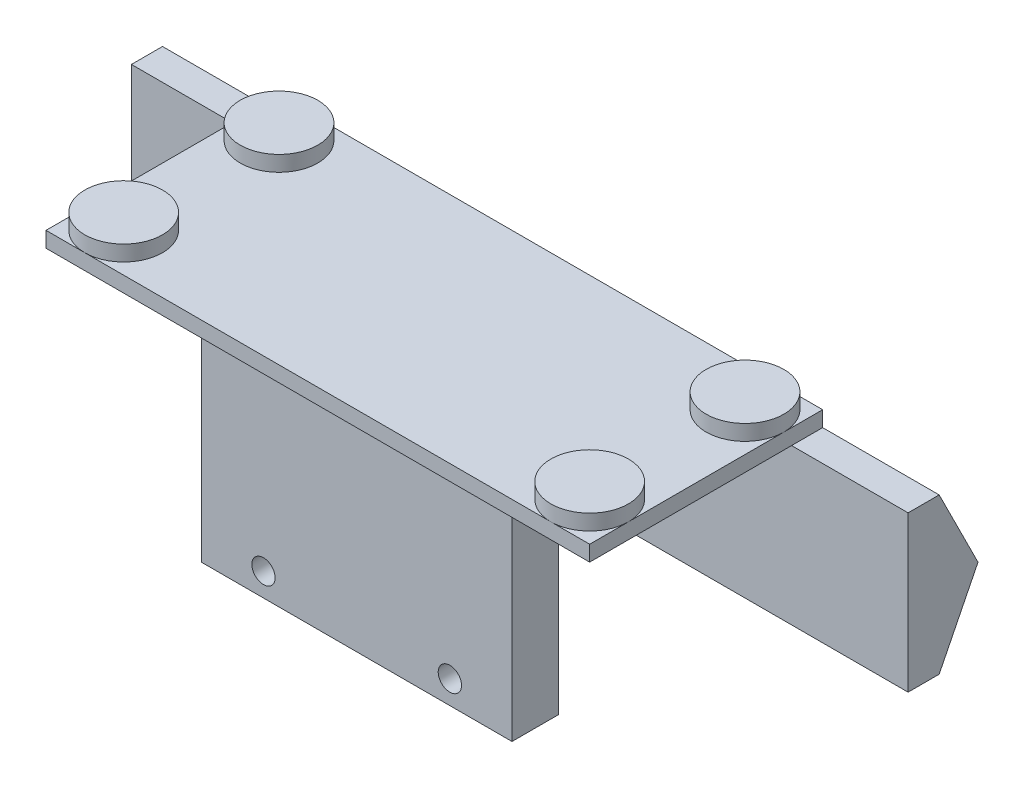
SolidWorks part; units mm, degrees
ref_plane "前视基准面" through (0, 0, 0) normal (0, 0, 1) x (1, 0, 0)
ref_plane "上视基准面" through (0, 0, 0) normal (0, 1, 0) x (1, 0, 0)
ref_plane "右视基准面" through (0, 0, 0) normal (1, 0, 0) x (0, 0, -1)
sketch "草图1" plane through (0, 0, 0) normal (0, 1, 0) x (1, 0, 0)
  line L0 (0, 30) -> (0, 0)
  line L1 (0, 30) -> (70, 30)
  line L2 (0, 0) -> (70, 0)
  line L3 (70, 30) -> (70, 0)
  point P8 (0, 0)
  point P13 (0, 0)
  point P16 (0, 0)
extrude "凸台-拉伸1" add sketch "草图1" along normal blind 2
sketch "草图2" plane through (0, 0, 0) normal (0, 1, 0) x (1, 0, 0)
  circle A0 centre (5, 25) radius 5
  circle A1 centre (5, 5) radius 5
  circle A2 centre (65, 25) radius 5
  circle A3 centre (65, 5) radius 5
  point P8 (-30, 10)
  point P9 (0, 0)
  point P10 (0, 0)
  point P11 (0, 0)
  point P12 (0, 0)
extrude "凸台-拉伸2" add sketch "草图2" along normal blind 4
sketch "草图3" plane through (0, 0, -30) normal (0, 0, -1) x (-1, 0, 0)
  line L0 (-85, 0) -> (-85, -20)
  line L1 (-85, 0) -> (15, 0)
  line L2 (-85, -20) -> (15, -20)
  line L3 (15, 0) -> (15, -20)
  point P0 (-70, 0)
extrude "凸台-拉伸3" add sketch "草图3" against normal blind 4
sketch "草图5" plane through (-15, 0, 0) normal (-1, 0, 0) x (0, 0, 1)
  line L0 (-30, -20) -> (-30, 0) construction
  line L1 (-30, 0) -> (-35, -10)
  line L2 (-35, -10) -> (-30, -20)
  line L3 (-30, -20) -> (-30, 0)
  point P0 (-30, 0)
  point P1 (-30, -20)
  point P3 (-30, -10)
  point P5 (-35, -10)
extrude "凸台-拉伸5" add sketch "草图5" against normal blind 100
ref_plane "基准面1" through (0, 0, -11) normal (0, 0, 1) x (1, 0, 0)
sketch "草图7" plane through (0, 0, -11) normal (0, 0, 1) x (1, 0, 0)
  line L0 (15, 0) -> (15, -30)
  line L1 (15, 0) -> (55, 0)
  line L2 (15, -30) -> (55, -30)
  line L3 (55, 0) -> (55, -30)
  line L4 (0, 0) -> (70, 0) construction
  point P4 (0, 0)
  point P6 (0, 0)
  point P7 (0, 0)
extrude "凸台-拉伸7" add sketch "草图7" along normal blind 6
sketch "草图8" plane through (0, 0, -5) normal (0, 0, 1) x (1, 0, 0)
  circle A0 centre (23, -3) radius 1.5
  circle A1 centre (47, -3) radius 1.5
  circle A2 centre (23, -27) radius 1.5
  circle A3 centre (47, -27) radius 1.5
  point P2 (0, 0)
  point P3 (0, 0)
  point P6 (0, 0)
  point P7 (0, 0)
  point P10 (0, 0)
  point P11 (0, 0)
  point P12 (0, 0)
  point P15 (0, 0)
extrude "切除-拉伸1" cut sketch "草图8" against normal up to next
sketch "草图10" plane through (0, 0, -26) normal (0, 0, 1) x (1, 0, 0)
  circle A0 centre (35, -15) radius 14
extrude "切除-拉伸2" cut sketch "草图10" against normal up to next
